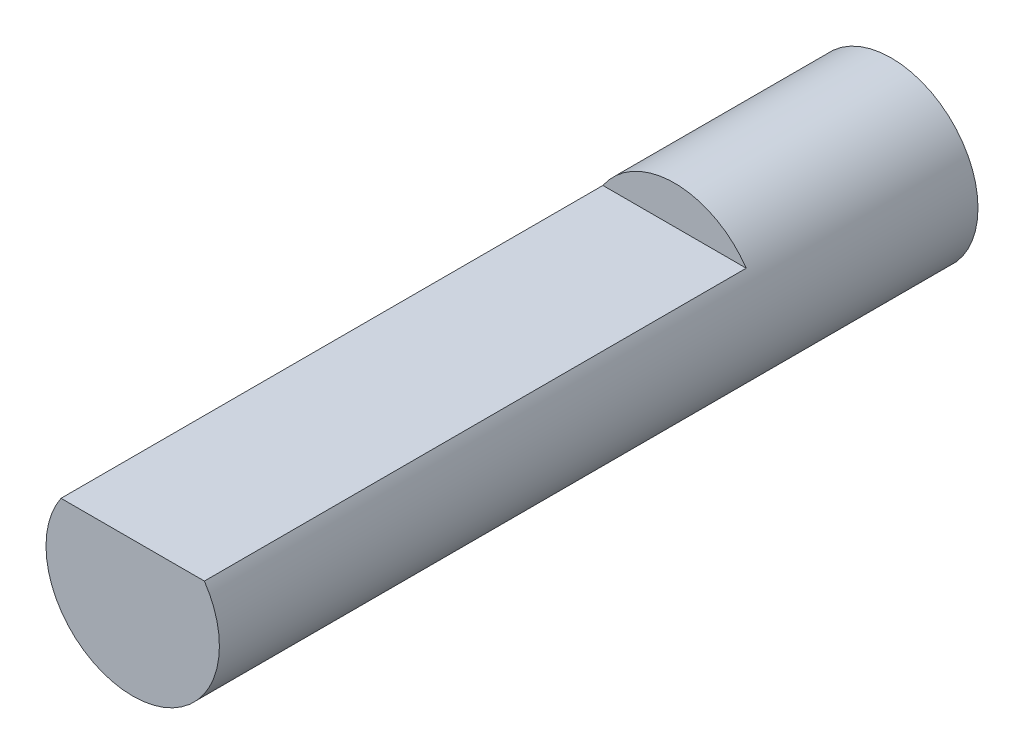
SolidWorks part; units mm, degrees
ref_plane "Front Plane" through (0, 0, 0) normal (0, 0, 1) x (1, 0, 0)
ref_plane "Top Plane" through (0, 0, 0) normal (0, 1, 0) x (1, 0, 0)
ref_plane "Right Plane" through (0, 0, 0) normal (1, 0, 0) x (0, 0, -1)
sketch "Sketch1" plane through (0, 0, 0) normal (0, 0, 1) x (1, 0, 0)
  circle A0 centre (0, 0) radius 1.6
  dimension "D1" = 3.2
extrude "Boss-Extrude1" add sketch "Sketch1" along normal blind 14
sketch "Sketch3" plane through (0, 0, 14) normal (0, 0, 1) x (1, 0, 0)
  line L0 (-1.3229, 0.9) -> (1.3229, 0.9)
  circle A0 centre (0, 0) radius 1.6 construction
  circle A1 centre (0, 0) radius 1.6 construction
  circle A2 centre (0, 0) radius 1.6
  circle M1 centre (0, 0) radius 1.6
  dimension "D1" = 0.9
extrude "Cut-Extrude1" cut sketch "Sketch3" against normal blind 10 contours L0 M1
